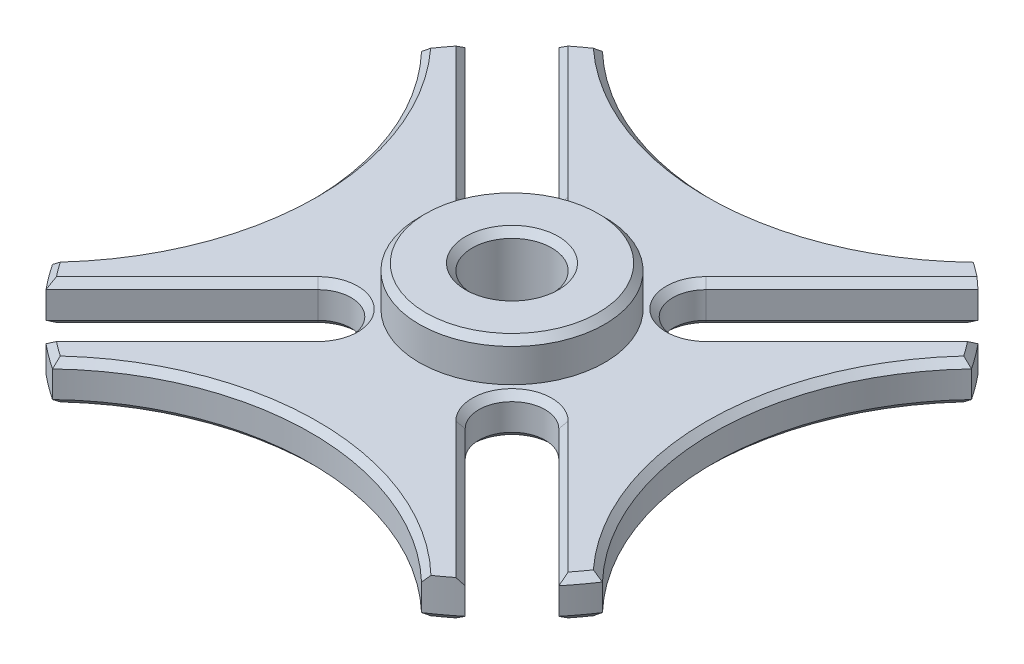
SolidWorks part; units mm, degrees
ref_plane "Front Plane" through (0, 0, 0) normal (0, 0, 1) x (1, 0, 0)
ref_plane "Top Plane" through (0, 0, 0) normal (0, 1, 0) x (1, 0, 0)
ref_plane "Right Plane" through (0, 0, 0) normal (1, 0, 0) x (0, 0, -1)
sketch "Sketch1" plane through (0, 0, 0) normal (0, 1, 0) x (1, 0, 0)
  line L3 (5.5546, 9.0901) -> (15.8213, 19.3568)
  line L4 (19.3568, 15.8213) -> (9.0901, 5.5546)
  line L6 (9.0901, -5.5546) -> (19.3568, -15.8213)
  line L7 (15.8213, -19.3568) -> (5.5546, -9.0901)
  line L8 (-5.5546, -9.0901) -> (-15.8213, -19.3568)
  line L9 (-19.3568, -15.8213) -> (-9.0901, -5.5546)
  line L10 (-9.0901, 5.5546) -> (-19.3568, 15.8213)
  line L11 (-15.8213, 19.3568) -> (-5.5546, 9.0901)
  circle A0 centre (0, 0) radius 3
  arc A1 (-20.7587, -13.9311) -> (-19.3548, -15.8237) centre (0, 0) ccw
  arc A2 (13.9311, -20.7587) -> (15.8237, -19.3548) centre (0, 0) ccw
  arc A3 (5.5546, 9.0901) -> (9.0901, 5.5546) centre (7.3223, 7.3223) ccw
  arc A5 (20.7587, 13.9311) -> (20.7587, -13.9311) centre (35.3553, 0) ccw
  arc A6 (9.0901, -5.5546) -> (5.5546, -9.0901) centre (7.3223, -7.3223) ccw
  arc A8 (-5.5546, -9.0901) -> (-9.0901, -5.5546) centre (-7.3223, -7.3223) ccw
  arc A10 (-9.0901, 5.5546) -> (-5.5546, 9.0901) centre (-7.3223, 7.3223) ccw
  arc A12 (13.9311, -20.7587) -> (-13.9311, -20.7587) centre (0, -35.3553) ccw
  arc A13 (-20.7587, -13.9311) -> (-20.7587, 13.9311) centre (-35.3553, 0) ccw
  arc A14 (-13.9311, 20.7587) -> (13.9311, 20.7587) centre (0, 35.3553) ccw
  arc A15 (-13.9311, 20.7587) -> (-15.8237, 19.3548) centre (0, 0) ccw
  arc A16 (-19.3548, 15.8237) -> (-20.7587, 13.9311) centre (0, 0) ccw
  arc A19 (-15.8237, -19.3548) -> (-13.9311, -20.7587) centre (0, 0) ccw
  arc A21 (19.3568, -15.8213) -> (20.7587, -13.9311) centre (0, 0) ccw
  arc A23 (20.7587, 13.9311) -> (19.3568, 15.8213) centre (0, 0) ccw
  arc A24 (15.8237, 19.3548) -> (13.9311, 20.7587) centre (0, 0) ccw
  point P45 (0, 0)
  point P56 (0, 0)
  dimension "D5" = 4
  dimension "D1" = 6
  dimension "D6" = 4
extrude "Boss-Extrude1" add sketch "Sketch1" along normal blind 3 contours L3 A24 A14 A15 L11 A10 L10 A16 A13 A1 L9 A8 L8 A19 A12 A2 L7 A6 L6 A21 A5 A23 L4 A3 A0
sketch "Sketch2" plane through (0, 3, 0) normal (0, 1, 0) x (1, 0, 0)
  line L8 (5.5546, 9.0901) -> (15.8213, 19.3568)
  line L9 (-15.8213, 19.3568) -> (-5.5546, 9.0901)
  line L10 (-9.0901, 5.5546) -> (-19.3568, 15.8213)
  line L11 (-19.3568, -15.8213) -> (-9.0901, -5.5546)
  line L12 (-5.5546, -9.0901) -> (-15.8213, -19.3568)
  line L13 (15.8213, -19.3568) -> (5.5546, -9.0901)
  line L14 (9.0901, -5.5546) -> (19.3568, -15.8213)
  line L15 (19.3568, 15.8213) -> (9.0901, 5.5546)
  line L16 (5.5546, 9.0901) -> (15.8213, 19.3568)
  line L17 (-15.8213, 19.3568) -> (-5.5546, 9.0901)
  line L18 (-9.0901, 5.5546) -> (-19.3568, 15.8213)
  line L19 (-19.3568, -15.8213) -> (-9.0901, -5.5546)
  line L20 (-5.5546, -9.0901) -> (-15.8213, -19.3568)
  line L21 (15.8213, -19.3568) -> (5.5546, -9.0901)
  line L22 (9.0901, -5.5546) -> (19.3568, -15.8213)
  line L23 (19.3568, 15.8213) -> (9.0901, 5.5546)
  circle A0 centre (0, 0) radius 7
  arc A16 (15.8213, 19.3568) -> (13.9311, 20.7587) centre (0, 0) ccw
  arc A17 (-13.9311, 20.7587) -> (13.9311, 20.7587) centre (0, 35.3553) ccw
  arc A18 (-13.9311, 20.7587) -> (-15.8213, 19.3568) centre (0, 0) ccw
  arc A19 (-9.0901, 5.5546) -> (-5.5546, 9.0901) centre (-7.3223, 7.3223) ccw
  arc A20 (-19.3568, 15.8213) -> (-20.7587, 13.9311) centre (0, 0) ccw
  arc A21 (-20.7587, -13.9311) -> (-20.7587, 13.9311) centre (-35.3553, 0) ccw
  arc A22 (-20.7587, -13.9311) -> (-19.3568, -15.8213) centre (0, 0) ccw
  arc A23 (-5.5546, -9.0901) -> (-9.0901, -5.5546) centre (-7.3223, -7.3223) ccw
  arc A24 (-15.8213, -19.3568) -> (-13.9311, -20.7587) centre (0, 0) ccw
  arc A25 (13.9311, -20.7587) -> (-13.9311, -20.7587) centre (0, -35.3553) ccw
  arc A26 (13.9311, -20.7587) -> (15.8213, -19.3568) centre (0, 0) ccw
  arc A27 (9.0901, -5.5546) -> (5.5546, -9.0901) centre (7.3223, -7.3223) ccw
  arc A28 (19.3568, -15.8213) -> (20.7587, -13.9311) centre (0, 0) ccw
  arc A29 (20.7587, 13.9311) -> (20.7587, -13.9311) centre (35.3553, 0) ccw
  arc A30 (20.7587, 13.9311) -> (19.3568, 15.8213) centre (0, 0) ccw
  arc A31 (5.5546, 9.0901) -> (9.0901, 5.5546) centre (7.3223, 7.3223) ccw
  arc A32 (15.8213, 19.3568) -> (13.9311, 20.7587) centre (0, 0) ccw
  arc A33 (-13.9311, 20.7587) -> (13.9311, 20.7587) centre (0, 35.3553) ccw
  arc A34 (-13.9311, 20.7587) -> (-15.8213, 19.3568) centre (0, 0) ccw
  arc A35 (-9.0901, 5.5546) -> (-5.5546, 9.0901) centre (-7.3223, 7.3223) ccw
  arc A36 (-19.3568, 15.8213) -> (-20.7587, 13.9311) centre (0, 0) ccw
  arc A37 (-20.7587, -13.9311) -> (-20.7587, 13.9311) centre (-35.3553, 0) ccw
  arc A38 (-20.7587, -13.9311) -> (-19.3568, -15.8213) centre (0, 0) ccw
  arc A39 (-5.5546, -9.0901) -> (-9.0901, -5.5546) centre (-7.3223, -7.3223) ccw
  arc A40 (-15.8213, -19.3568) -> (-13.9311, -20.7587) centre (0, 0) ccw
  arc A41 (13.9311, -20.7587) -> (-13.9311, -20.7587) centre (0, -35.3553) ccw
  arc A42 (13.9311, -20.7587) -> (15.8213, -19.3568) centre (0, 0) ccw
  arc A43 (9.0901, -5.5546) -> (5.5546, -9.0901) centre (7.3223, -7.3223) ccw
  arc A44 (19.3568, -15.8213) -> (20.7587, -13.9311) centre (0, 0) ccw
  arc A45 (20.7587, 13.9311) -> (20.7587, -13.9311) centre (35.3553, 0) ccw
  arc A46 (20.7587, 13.9311) -> (19.3568, 15.8213) centre (0, 0) ccw
  arc A47 (5.5546, 9.0901) -> (9.0901, 5.5546) centre (7.3223, 7.3223) ccw
  circle M25 centre (0, 0) radius 3
  dimension "D2" = 14
  dimension "D1" = 0
extrude "Boss-Extrude2" add sketch "Sketch2" along normal blind 3 contours A0 M25
chamfer "Chamfer1" distance 0.5 angle 45 49 edges at (0, 6, 7) (10.6879, 3, 14.2235) (5.5546, 3, 5.5546) (14.2235, 3, 10.6879) (20.08, 3, 14.8927) (15.1777, 3, 0) (20.08, 3, -14.8927) (14.2235, 3, -10.6879) (5.5546, 3, -5.5546) (10.6879, 3, -14.2235) (0, 3, 15.1777) (-14.8927, 3, 20.08) (-10.6879, 3, 14.2235) (-5.5546, 3, 5.5546) (-14.2235, 3, 10.6879) (-20.08, 3, 14.8927) (-15.1777, 3, 0) (-20.08, 3, -14.8927) (0, 3, -15.1777) (-14.8927, 3, -20.08) (-10.6879, 3, -14.2235) (-5.5546, 3, -5.5546) (-14.2235, 3, -10.6879) (0, 6, 3) (0, 0, 3) (20.08, 0, 14.8927) (14.2235, 0, 10.6879) (5.5546, 0, 5.5546) (10.6879, 0, 14.2235) (14.8927, 0, 20.08) (0, 0, 15.1777) (-14.8927, 0, 20.08) (-10.6879, 0, 14.2235) (-5.5546, 0, 5.5546) (-14.2235, 0, 10.6879) (-20.08, 0, 14.8927) (-15.1777, 0, 0) (-20.08, 0, -14.8927) (-14.2235, 0, -10.6879) (-5.5546, 0, -5.5546) (-10.6879, 0, -14.2235) (-14.8927, 0, -20.08) (0, 0, -15.1777) (14.8927, 0, -20.08) (10.6879, 0, -14.2235) (5.5546, 0, -5.5546) (14.2235, 0, -10.6879) (20.08, 0, -14.8927) (15.1777, 0, 0)
